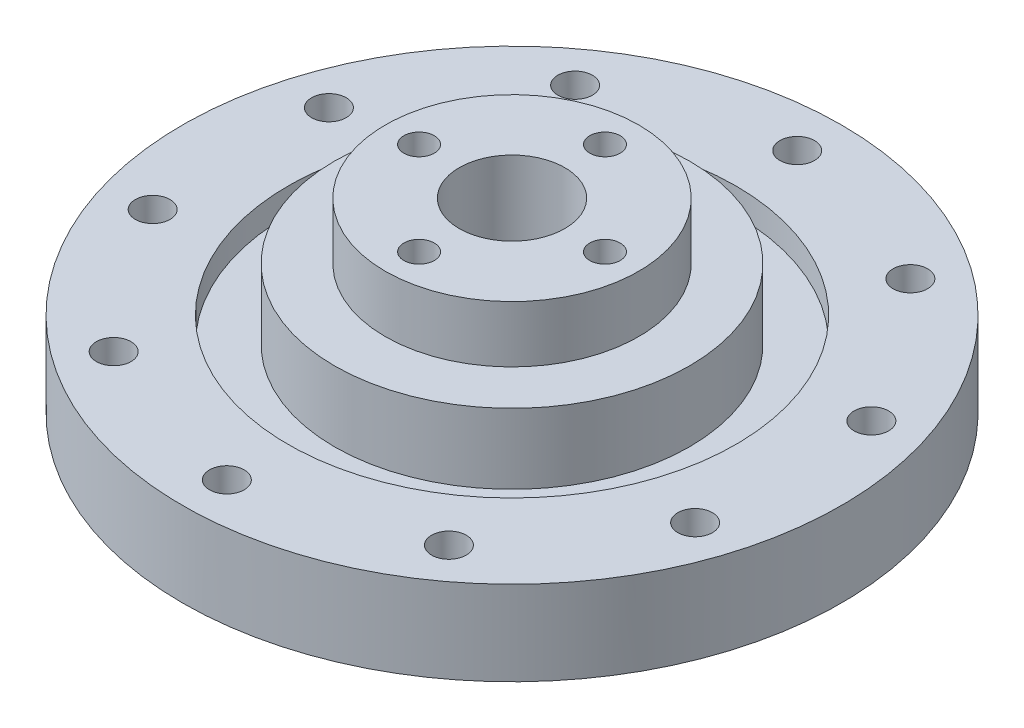
SolidWorks part; units mm, degrees
ref_plane "Front Plane" through (0, 0, 0) normal (0, 0, 1) x (1, 0, 0)
ref_plane "Top Plane" through (0, 0, 0) normal (0, 1, 0) x (1, 0, 0)
ref_plane "Right Plane" through (0, 0, 0) normal (1, 0, 0) x (0, 0, -1)
sketch "Sketch1" plane through (0, 0, 0) normal (0, 1, 0) x (1, 0, 0)
  circle A0 centre (0, 0) radius 39
  dimension "D1" = 78
extrude "Boss-Extrude1" add sketch "Sketch1" along normal blind 7
sketch "Sketch3" plane through (0, 7, 0) normal (0, 1, 0) x (1, 0, 0)
  circle A0 centre (0, 0) radius 17.5
  dimension "D1" = 35
extrude "Boss-Extrude2" add sketch "Sketch3" along normal blind 1
sketch "Sketch4" plane through (0, 8, 0) normal (0, 1, 0) x (1, 0, 0)
  circle A0 centre (0, 0) radius 15
  dimension "D1" = 30
extrude "Boss-Extrude3" add sketch "Sketch4" along normal blind 14 contours A0
sketch "Sketch5" plane through (0, 22, 0) normal (0, 1, 0) x (1, 0, 0)
  circle A0 centre (0, 0) radius 6.25
  circle A1 centre (0, 11) radius 1.8
  circle A2 centre (11, 0) radius 1.8
  circle A3 centre (0, -11) radius 1.8
  circle A4 centre (-11, 0) radius 1.8
  dimension "D1" = 12.5
  dimension "D3" = 3.6
  dimension "D2" = 11
  dimension "D4" = 4
extrude "Cut-Extrude1" cut sketch "Sketch5" against normal through all
hole_wizard "CSK for M4 Countersunk Flat Head Screw1" positions "3DSketch1" profile "Sketch6" countersink size "M4" standard "ISO" end condition through all
sketch3d "3DSketch1"
  line L0 (11, 0, 0) -> (11, 22, 0) construction
  line L1 (0, 0, -11) -> (0, 22, -11) construction
  line L2 (-11, 0, 0) -> (-11, 22, 0) construction
  line L3 (0, 0, 11) -> (0, 22, 11) construction
  point P0 (11, 0, 0)
  point P4 (0, 0, -11)
  point P8 (-11, 0, 0)
  point P12 (0, 0, 11)
sketch "Sketch6" plane through (11, 0, 0) normal (1, 0, 0) x (0, 0, -1)
  line L0 (0, 0) -> (0, 22)
  line L1 (0, 22) -> (1.75, 22)
  line L2 (1.75, 22) -> (1.75, 2.8)
  line L3 (1.75, 2.8) -> (4.55, 0)
  line L5 (4.55, 0) -> (0, 0)
  line L6 (-1.75, 2.8) -> (-4.55, 0) construction
  line L11 (0, -6.35) -> (0, 107.95) construction
  dimension "Thru Hole Dia." = 3.5
  dimension "Thru Hole Depth" = 22
  dimension "Near C'Sink Dia." = 9.1
  dimension "Near C'Sink Angle" = 90
sketch "Sketch7" plane through (0, 7, 0) normal (0, 1, 0) x (1, 0, 0)
  circle A0 centre (0, 0) radius 26.5
  circle A1 centre (0, 0) radius 28.5
  dimension "D1" = 53
  dimension "D2" = 2
extrude "Boss-Extrude4" add sketch "Sketch7" along normal blind 10.5
sketch "Sketch8" plane through (0, 7, 0) normal (0, 1, 0) x (1, 0, 0)
  circle A0 centre (0, 0) radius 17.5 construction
  circle A1 centre (0, 0) radius 26.5
  circle A2 centre (0, 0) radius 26.5
  circle A3 centre (0, 0) radius 17.5
  dimension "D1" = 0
extrude "Cut-Extrude2" cut sketch "Sketch8" against normal blind 1
sketch "Sketch9" plane through (0, 7, 0) normal (0, 1, 0) x (1, 0, 0)
  line L0 (0, 0) -> (0, 33.75) construction
  circle A0 centre (0, 33.75) radius 2.05
  circle A1 centre (19.8378, 27.3043) radius 2.05
  circle A2 centre (32.0982, 10.4293) radius 2.05
  circle A3 centre (32.0982, -10.4293) radius 2.05
  circle A4 centre (19.8378, -27.3043) radius 2.05
  circle A5 centre (0, -33.75) radius 2.05
  circle A6 centre (-19.8378, -27.3043) radius 2.05
  circle A7 centre (-32.0982, -10.4293) radius 2.05
  circle A8 centre (-32.0982, 10.4293) radius 2.05
  circle A9 centre (-19.8378, 27.3043) radius 2.05
  dimension "D2" = 4.1
  dimension "D1" = 33.75
  dimension "D3" = 10
extrude "Cut-Extrude3" cut sketch "Sketch9" against normal through all
sketch "Sketch10" plane through (0, 7, 0) normal (0, 1, 0) x (1, 0, 0)
  line L0 (-33.5, 0) -> (0, 0) construction
  line L1 (-33.5, 3) -> (-28.3417, 3)
  line L2 (-33.5, -3) -> (-28.3417, -3)
  arc A0 (-33.5, 3) -> (-33.5, -3) centre (-33.5, 0) ccw
  circle A1 centre (0, 0) radius 28.5 construction
  arc A2 (-28.3417, 3) -> (-28.3417, -3) centre (0, 0) ccw
  dimension "D2" = 6
  dimension "D1" = 33.5
extrude "Boss-Extrude5" add sketch "Sketch10" along normal up to surface (10.5 mm away) up to face at (0, 17.5, 28.5)
sketch "Sketch11" plane through (0, 7, 0) normal (0, 1, 0) x (1, 0, 0)
  line L0 (0, 0) -> (35, 0) construction
  line L1 (35, 4.55) -> (38.7337, 4.55)
  line L2 (35, -4.55) -> (38.7337, -4.55)
  arc A0 (35, 4.55) -> (35, -4.55) centre (35, 0) ccw
  circle A1 centre (0, 0) radius 39 construction
  arc A2 (38.7337, -4.55) -> (38.7337, 4.55) centre (0, 0) ccw
  dimension "D1" = 9.1
  dimension "D2" = 35
extrude "Cut-Extrude4" cut sketch "Sketch11" against normal through all contours L1 A2 L2 A0
fillet "Fillet1" radius 1 2 edges at (38.7337, 3.5, 4.55) (38.7337, 3.5, -4.55)
sketch "Sketch12" plane through (0, 0, 0) normal (0, -1, 0) x (1, 0, 0)
  circle A0 centre (0, 0) radius 39
  circle A1 centre (0, 33.75) radius 2.05
  circle A2 centre (0, 0) radius 19.1057
  circle A3 centre (19.8378, 27.3043) radius 2.05
  circle A4 centre (32.0982, 10.4293) radius 2.05
  circle A5 centre (32.0982, -10.4293) radius 2.05
  circle A6 centre (19.8378, -27.3043) radius 2.05
  circle A7 centre (0, -33.75) radius 2.05
  circle A8 centre (-19.8378, -27.3043) radius 2.05
  circle A9 centre (-32.0982, -10.4293) radius 2.05
  circle A10 centre (-32.0982, 10.4293) radius 2.05
  circle A11 centre (-19.8378, 27.3043) radius 2.05
  point P27 (0, 0)
  dimension "D1" = 10
extrude "Boss-Extrude6" add sketch "Sketch12" against normal blind 10
sketch "Sketch18" plane through (0, 6, 0) normal (0, 1, 0) x (1, 0, 0)
  circle A0 centre (0, 0) radius 15
  circle A1 centre (0, 0) radius 21
  dimension "D1" = 42
  dimension "D2" = 30
extrude "Boss-Extrude9" add sketch "Sketch18" along normal blind 9.3
sketch "Sketch19" plane through (0, 10, 0) normal (0, 1, 0) x (1, 0, 0)
  circle A0 centre (0, 0) radius 21
  circle A1 centre (0, 0) radius 26.5
extrude "Cut-Extrude5" cut sketch "Sketch19" against normal blind 3
sketch "Sketch20" plane through (0, 17.5, 0) normal (0, 1, 0) x (1, 0, 0)
  circle A0 centre (0, 0) radius 28.5
  circle A1 centre (0, 0) radius 36.5
extrude "Cut-Extrude6" cut sketch "Sketch20" against normal up to surface (7.5 mm away) up to face at (0, 10, -39)
sketch "Sketch21" plane through (0, 22, 0) normal (0, 1, 0) x (1, 0, 0)
  circle A0 centre (0, 0) radius 28.5
  circle A1 centre (0, 0) radius 26.5
extrude "Cut-Extrude7" cut sketch "Sketch21" against normal up to surface (12 mm away) up to face at (0, 10, -39)
equation "\"3mmmm\"=9"
